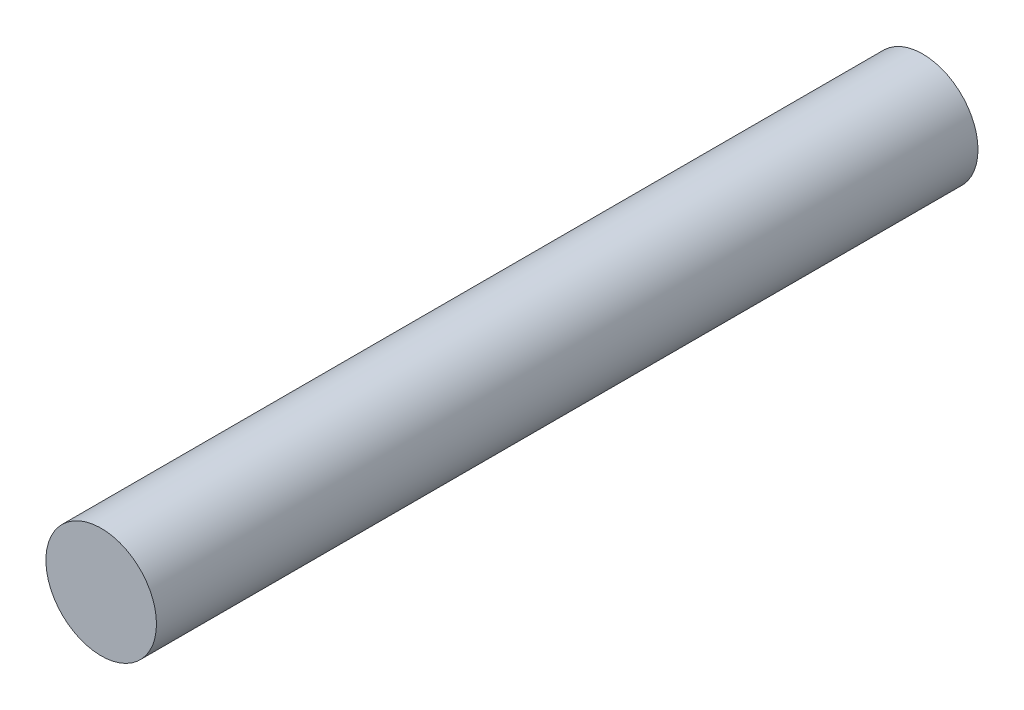
SolidWorks part; units mm, degrees
material "PET"
ref_plane "Front Plane" through (0, 0, 0) normal (0, 0, 1) x (1, 0, 0)
ref_plane "Top Plane" through (0, 0, 0) normal (0, 1, 0) x (1, 0, 0)
ref_plane "Right Plane" through (0, 0, 0) normal (1, 0, 0) x (0, 0, -1)
sketch "Sketch2" plane through (0, 0, 0) normal (0, 0, 1) x (1, 0, 0)
  circle A0 centre (0, 0) radius 9.144
  dimension "D1" = 18.288
extrude "Thicker Section" add sketch "Sketch2" along normal blind 135.89
sketch "Sketch3" plane through (0, 0, 135.89) normal (0, 0, 1) x (1, 0, 0)
  circle A0 centre (0, 0) radius 8.128
  dimension "D1" = 16.256
extrude "Smaller  Section" [suppressed] add sketch "Sketch3" along normal blind 124.46
fillet "Fillet1" [suppressed] radius 2.54
sketch "Sketch4" [suppressed] plane through (0, 0, 135.89) normal (0, 0, 1) x (1, 0, 0)
  circle A0 centre (0, 0) radius 2
  dimension "D1" = 4
extrude "Cut-Extrude1" [suppressed] cut sketch "Sketch4" against normal blind 19.05
